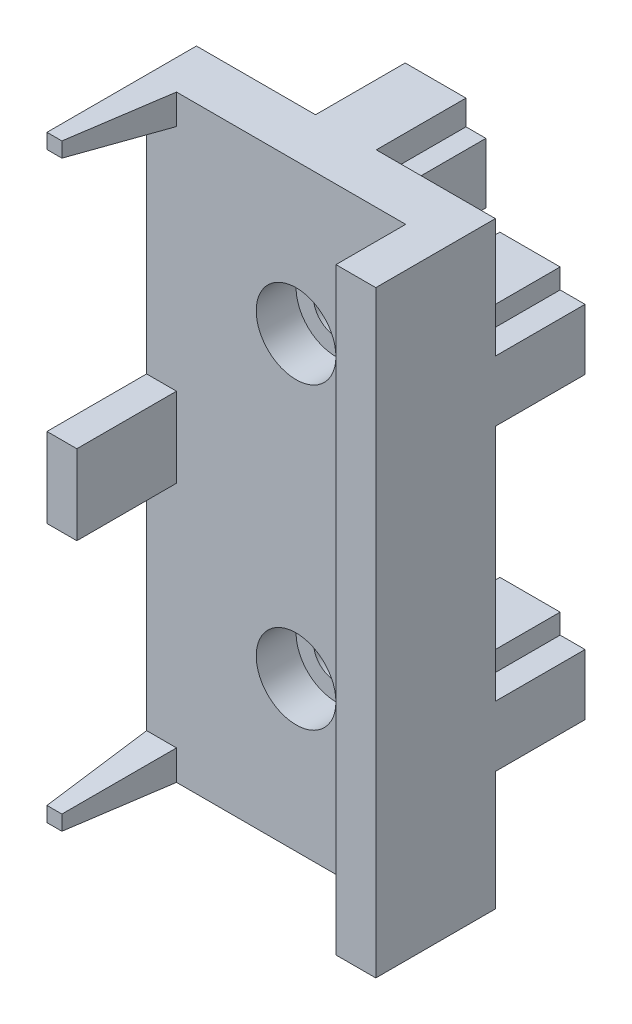
SolidWorks part; units mm, degrees
ref_plane "정면" through (0, 0, 0) normal (0, 0, 1) x (1, 0, 0)
ref_plane "윗면" through (0, 0, 0) normal (0, 1, 0) x (1, 0, 0)
ref_plane "우측면" through (0, 0, 0) normal (1, 0, 0) x (0, 0, -1)
sketch "스케치1" plane through (0, 0, 0) normal (0, 0, 1) x (1, 0, 0)
  line L1 (-15, 30) -> (15, 30)
  line L2 (-15, 30) -> (-15, -30)
  line L3 (-15, -30) -> (15, -30)
  line L4 (15, 30) -> (15, -30)
  line L5 (-15, 30) -> (15, -30) construction
  line L6 (-15, -30) -> (15, 30) construction
  point P0 (0, 0)
  dimension "D1" = 30
  dimension "D2" = 60
extrude "보스-돌출1" add sketch "스케치1" along normal blind 5
sketch "스케치2" plane through (0, 0, 5) normal (0, 0, 1) x (1, 0, 0)
  line L5 (15, 30) -> (-15, 30) construction
  line L10 (-15, -30) -> (-12, -30)
  line L11 (-15, -30) -> (-15, -27)
  line L12 (-15, -27) -> (-12, -27)
  line L13 (-12, -30) -> (-12, -27)
  line L14 (-15, 30) -> (-12, 30)
  line L15 (-15, 30) -> (-15, 27)
  line L16 (-15, 27) -> (-12, 27)
  line L17 (-12, 30) -> (-12, 27)
  line L18 (15, 30) -> (11, 30)
  line L19 (15, 30) -> (15, -30)
  line L20 (15, -30) -> (11, -30)
  line L21 (11, 30) -> (11, -30)
  line L22 (-15, -30) -> (15, -30) construction
  line L23 (-15, 30) -> (-15, -30) construction
  line L24 (-15, 4) -> (-12, 4)
  line L25 (-15, 4) -> (-15, -4)
  line L26 (-15, -4) -> (-12, -4)
  line L27 (-12, 4) -> (-12, -4)
  line L28 (-15, 4) -> (-12, -4) construction
  line L29 (-15, -4) -> (-12, 4) construction
  point P0 (-13.5, 0)
  dimension "D1" = 3
  dimension "D2" = 8
  dimension "D3" = 0
  dimension "D4" = 3
  dimension "D5" = 3
  dimension "D6" = 4
extrude "보스-돌출2" add sketch "스케치2" along normal blind 10
ref_plane "평면1" through (0, 0, 0) normal (0, -1, 0) x (-1, 0, 0)
sketch "스케치3" plane through (-12, 0, 0) normal (1, 0, 0) x (0, 0, -1)
  line L0 (-15, -28.5) -> (-5, -27)
  line L1 (-15, -30) -> (-15, -27) construction
  line L2 (-5, -27) -> (-15, -27)
  line L3 (-15, -27) -> (-15, -28.5)
extrude "컷-돌출1" cut sketch "스케치3" against normal through all
sketch "스케치4" plane through (0, -30, 0) normal (0, -1, 0) x (1, 0, 0)
  line L6 (-13.5, 15) -> (-12, 15)
  line L7 (-15, 15) -> (-12, 15) construction
  line L8 (-12, 15) -> (-12, 5)
  line L9 (-12, 5) -> (-13.5, 15)
extrude "컷-돌출3" cut sketch "스케치4" against normal blind 7
mirror "대칭 복사1" about plane through (0, 0, 0) normal (0, -1, 0) of "컷-돌출3", "컷-돌출1"
sketch "스케치5" plane through (0, 30, 0) normal (0, 1, 0) x (1, 0, 0)
  line L0 (15, -15) -> (15, 0) construction
  line L1 (11, -15) -> (15, -15)
  line L2 (11, -15) -> (11, -12)
  line L3 (11, -12) -> (15, -12)
  line L4 (15, -15) -> (15, -12)
  dimension "D1" = 3
extrude "컷-돌출4" cut sketch "스케치5" against normal through all
hole_wizard "M4 소켓 머리 캡 나사용 카운터보어1" positions "스케치7" profile "스케치8" counterbore size "M4" standard "KS" end condition through all
sketch "스케치7" plane through (0, 0, 5) normal (0, 0, 1) x (1, 0, 0)
  line L0 (11, 30) -> (-12, 30) construction
  line L1 (-15, 27) -> (-15, 4) construction
  line L2 (-12, -30) -> (11, -30) construction
  line L3 (-15, -4) -> (-15, -27) construction
  point P0 (0, -15)
  point P2 (0, 15)
  dimension "D1" = 15
  dimension "D2" = 15
  dimension "D3" = 15
  dimension "D4" = 15
sketch "스케치8" plane through (0, -15, 5) normal (1, 0, 0) x (0, -1, 0)
  line L0 (0, 0) -> (0, 5)
  line L1 (0, 5) -> (2.25, 5)
  line L3 (2.25, 5) -> (2.25, 4)
  line L4 (2.25, 4) -> (4, 4)
  line L5 (4, 4) -> (4, 0)
  line L7 (4, 0) -> (0, 0)
  line L11 (0, -6.35) -> (0, 107.95) construction
  dimension "관통 구멍 지름" = 4.5
  dimension "관통 구멍 깊이" = 5
  dimension "카운터보어 지름" = 8
  dimension "카운터보어 깊이" = 4
sketch "스케치9" plane through (0, 0, 0) normal (0, 0, -1) x (-1, 0, 0)
  line L6 (-15, 30) -> (15, 30) construction
  line L25 (-8.1804, 19.5) -> (10.0625, 19.5) construction
  line L50 (-3.05, 30) -> (3.05, 30)
  line L51 (3.05, 30) -> (3.05, 27.5)
  line L52 (3.05, 27.5) -> (5.05, 27.5)
  line L53 (5.05, 27.5) -> (5.05, 21.455)
  line L54 (-3.05, 30) -> (-3.05, 27.5)
  line L55 (-3.05, 27.5) -> (-5.05, 27.5)
  line L56 (-5.05, 27.5) -> (-5.05, 21.455)
  line L64 (-15, -30) -> (-15, 30) construction
  line L65 (15, 18.05) -> (15, 11.95)
  line L66 (15, 11.95) -> (12.5, 11.95)
  line L67 (12.5, 11.95) -> (12.5, 9.95)
  line L68 (12.5, 9.95) -> (6.455, 9.95)
  line L69 (15, 18.05) -> (12.5, 18.05)
  line L70 (12.5, 18.05) -> (12.5, 20.05)
  line L71 (12.5, 20.05) -> (6.455, 20.05)
  line L72 (4.5, 23.1804) -> (4.5, 4.9375) construction
  line L75 (-3.05, 2.5) -> (-5.05, 2.5)
  line L76 (-5.05, 2.5) -> (-5.05, 8.545)
  line L78 (3.05, 2.5) -> (5.05, 2.5)
  line L79 (5.05, 2.5) -> (5.05, 8.545)
  line L80 (8.1804, 10.5) -> (-10.0625, 10.5) construction
  line L81 (-15, 11.95) -> (-15, 18.05)
  line L82 (-15, 18.05) -> (-12.5, 18.05)
  line L83 (-12.5, 18.05) -> (-12.5, 20.05)
  line L84 (-12.5, 20.05) -> (-6.455, 20.05)
  line L85 (-15, 11.95) -> (-12.5, 11.95)
  line L86 (-12.5, 11.95) -> (-12.5, 9.95)
  line L87 (-12.5, 9.95) -> (-6.455, 9.95)
  line L88 (-4.5, 6.8196) -> (-4.5, 25.0625) construction
  line L89 (-6.1352, 0) -> (6.1352, 0) construction
  line L90 (-5.05, -27.5) -> (-5.05, -21.455)
  line L91 (-3.05, -27.5) -> (-5.05, -27.5)
  line L92 (-3.05, -30) -> (-3.05, -27.5)
  line L93 (5.05, -27.5) -> (5.05, -21.455)
  line L94 (3.05, -27.5) -> (5.05, -27.5)
  line L95 (3.05, -30) -> (3.05, -27.5)
  line L96 (-3.05, -30) -> (3.05, -30)
  line L97 (-12.5, -9.95) -> (-6.455, -9.95)
  line L98 (-12.5, -11.95) -> (-12.5, -9.95)
  line L99 (-15, -11.95) -> (-12.5, -11.95)
  line L100 (-12.5, -20.05) -> (-6.455, -20.05)
  line L101 (-12.5, -18.05) -> (-12.5, -20.05)
  line L102 (-15, -18.05) -> (-12.5, -18.05)
  line L103 (-15, -11.95) -> (-15, -18.05)
  line L104 (5.05, -2.5) -> (5.05, -8.545)
  line L105 (3.05, -2.5) -> (5.05, -2.5)
  line L107 (-5.05, -2.5) -> (-5.05, -8.545)
  line L108 (-3.05, -2.5) -> (-5.05, -2.5)
  line L111 (12.5, -20.05) -> (6.455, -20.05)
  line L112 (12.5, -18.05) -> (12.5, -20.05)
  line L113 (15, -18.05) -> (12.5, -18.05)
  line L114 (12.5, -9.95) -> (6.455, -9.95)
  line L115 (12.5, -11.95) -> (12.5, -9.95)
  line L116 (15, -11.95) -> (12.5, -11.95)
  line L117 (15, -18.05) -> (15, -11.95)
  line L118 (3.05, 0) -> (-3.05, 0) [skipped]
  line L119 (3.05, 0) -> (-3.05, 0) [skipped]
  line L120 (-3.05, 0) -> (-3.05, 2.5) [skipped]
  line L121 (-3.05, 0) -> (-3.05, -2.5) [skipped]
  line L122 (-3.05, 2.5) -> (-3.05, -2.5)
  line L123 (3.05, 2.5) -> (3.05, -2.5)
  line L124 (3.05, 0) -> (3.05, -2.5) [skipped]
  line L125 (3.05, 0) -> (3.05, 2.5) [skipped]
  circle A0 centre (0, 15) radius 2.25 construction
  arc A1 (-5.05, 21.455) -> (5.05, 21.455) centre (0, 27) ccw
  arc A2 (6.455, 20.05) -> (6.455, 9.95) centre (12, 15) ccw
  arc A3 (5.05, 8.545) -> (-5.05, 8.545) centre (0, 3) ccw
  arc A4 (-6.455, 9.95) -> (-6.455, 20.05) centre (-12, 15) ccw
  arc A5 (-5.05, -21.455) -> (5.05, -21.455) centre (0, -27) cw
  arc A6 (-6.455, -9.95) -> (-6.455, -20.05) centre (-12, -15) cw
  arc A7 (5.05, -8.545) -> (-5.05, -8.545) centre (0, -3) cw
  arc A8 (6.455, -20.05) -> (6.455, -9.95) centre (12, -15) cw
  point P9 (0, 30)
  point P54 (0, 15)
  point P93 (0, -15)
  dimension "D4" = 2.5
  dimension "D7" = 7.5
  dimension "D1" = 0
  dimension "D2" = 6.1
  dimension "D3" = 5.05
  dimension "D5" = 10.1
  dimension "D6" = 3.05
  dimension "D8" = 10.5
  dimension "D9" = 4
  dimension "D10" = 3.05
  dimension "D11" = 4
extrude "보스-돌출3" add sketch "스케치9" along normal blind 10
chamfer "모따기1" distance 1 angle 45 60 edges at (0, 30, -10) (-3.05, 28.75, -10) (3.05, 28.75, -10) (-4.05, 27.5, -10) (-5.05, 24.4775, -10) (0, 19.5, -10) (5.05, 24.4775, -10) (4.05, 27.5, -10) (-5.05, -24.4775, -10) (-4.05, -27.5, -10) (-3.05, -28.75, -10) (0, -30, -10) (3.05, -28.75, -10) (4.05, -27.5, -10) (5.05, -24.4775, -10) (0, -19.5, -10) (9.4775, -20.05, -10) (12.5, -19.05, -10) (13.75, -18.05, -10) (15, -15, -10) (13.75, -11.95, -10) (12.5, -10.95, -10) (9.4775, -9.95, -10) (4.5, -15, -10) (-9.4775, -9.95, -10) (-12.5, -10.95, -10) (-13.75, -11.95, -10) (-15, -15, -10) (-13.75, -18.05, -10) (-12.5, -19.05, -10) (-9.4775, -20.05, -10) (-4.5, -15, -10) (4.05, 2.5, -10) (5.05, 5.5225, -10) (0, 10.5, -10) (-5.05, 5.5225, -10) (-4.05, 2.5, -10) (-3.05, 0, -10) (-4.05, -2.5, -10) (-5.05, -5.5225, -10) (0, -10.5, -10) (5.05, -5.5225, -10) (4.05, -2.5, -10) (3.05, 0, -10) (-15, 15, -10) (-13.75, 11.95, -10) (-12.5, 10.95, -10) (-9.4775, 9.95, -10) (-4.5, 15, -10) (-9.4775, 20.05, -10) (-12.5, 19.05, -10) (-13.75, 18.05, -10) (15, 15, -10) (13.75, 18.05, -10) (12.5, 19.05, -10) (9.4775, 20.05, -10) (4.5, 15, -10) (9.4775, 9.95, -10) (12.5, 10.95, -10) (13.75, 11.95, -10)
